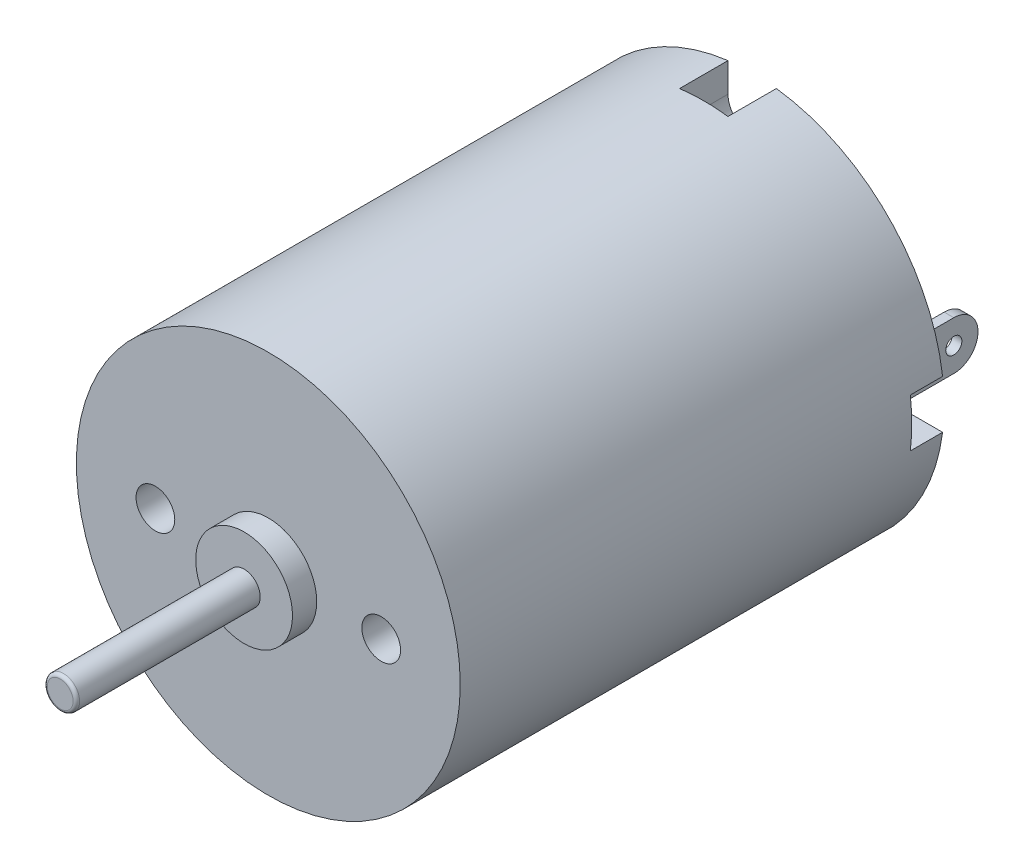
SolidWorks part; units mm, degrees
ref_plane "Alzado" through (0, 0, 0) normal (0, 0, 1) x (1, 0, 0)
ref_plane "Planta" through (0, 0, 0) normal (0, 1, 0) x (1, 0, 0)
ref_plane "Vista lateral" through (0, 0, 0) normal (1, 0, 0) x (0, 0, -1)
sketch "Croquis2" plane through (0, 0, 0) normal (0, 0, 1) x (1, 0, 0)
  circle A0 centre (0, 0) radius 11.9
  dimension "D1" = 23.8
extrude "Saliente-Extruir1" add sketch "Croquis2" along normal blind 30
sketch "Croquis3" plane through (0, 0, 30) normal (0, 0, 1) x (1, 0, 0)
  circle A0 centre (0, 0) radius 3
extrude "Saliente-Extruir2" add sketch "Croquis3" along normal blind 1.5
sketch "Croquis4" plane through (0, 0, 31.5) normal (0, 0, 1) x (1, 0, 0)
  circle A0 centre (0, 0) radius 1
  dimension "D1" = 2
extrude "Cortar-Extruir1" cut sketch "Croquis4" against normal through all
sketch "Croquis5" plane through (0, 0, 30) normal (0, 0, 1) x (1, 0, 0)
  line L0 (0, 0) -> (-5.8, 0) construction
  line L1 (0, 0) -> (5.8, 0)
  line L2 (-8.2, 0) -> (-5.8, 0) construction
  line L3 (5.8, 0) -> (8.2, 0) construction
  line L4 (-5.8, 0) -> (5.8, 0) construction
  circle A0 centre (-7, 0) radius 1.2
  circle A1 centre (7, 0) radius 1.2
  dimension "D1" = 2.4
  dimension "D2" = 5.8
  dimension "D3" = 5.8
extrude "Cortar-Extruir2" cut sketch "Croquis5" against normal blind 5 contours A1 | A0
sketch "Croquis7" plane through (0, 0, 0) normal (0, 0, -1) x (-1, 0, 0)
  circle A0 centre (0, 0) radius 4.5
  dimension "D1" = 9
extrude "Saliente-Extruir3" add sketch "Croquis7" along normal blind 1.7
sketch "Croquis8" plane through (0, 0, -1.7) normal (0, 0, -1) x (-1, 0, 0)
  circle A0 centre (0, 0) radius 1
  dimension "D1" = 2
extrude "Cortar-Extruir3" cut sketch "Croquis8" against normal up to next
sketch "Croquis9" plane through (0, 0, 0) normal (0, 0, -1) x (-1, 0, 0)
  line L0 (0, 0) -> (-9, 0) construction
  line L1 (-9, 0) -> (9, 0) construction
  line L2 (-9, 0) -> (-9, 1.5)
  line L3 (-9, 1.5) -> (-8.4, 1.5)
  line L4 (-8.4, 1.5) -> (-8.4, -1.5)
  line L5 (-8.4, -1.5) -> (-9, -1.5)
  line L6 (-9, -1.5) -> (-9, 0)
  line L7 (9, 0) -> (9, 1.5)
  line L8 (9, 1.5) -> (8.4, 1.5)
  line L9 (8.4, 1.5) -> (8.4, -1.5)
  line L10 (8.4, -1.5) -> (9, -1.5)
  line L11 (9, -1.5) -> (9, 0)
  dimension "D1" = 9
  dimension "D2" = 18
  dimension "D3" = 1.5
  dimension "D4" = 3
  dimension "D5" = 0.6
  dimension "D6" = 1.5
  dimension "D7" = 3
  dimension "D8" = 0.6
extrude "Saliente-Extruir4" add sketch "Croquis9" along normal blind 5
sketch "Croquis10" plane through (-9, 0, 0) normal (-1, 0, 0) x (0, 0, 1)
  line L0 (-5, -1.5) -> (-5, 1.5) construction
  line L1 (-3.5, -1.5) -> (-5, -1.5)
  line L2 (-5, -1.5) -> (-5, 1.5)
  line L3 (-5, 1.5) -> (-3.5, 1.5)
  arc A0 (-3.5, 1.5) -> (-3.5, -1.5) centre (-3.5, 0) ccw
  circle A1 centre (-3.5, 0) radius 0.5
  line M4 (0, 1.5) -> (-5, 1.5)
  line M5 (-5, 1.5) -> (-5, -1.5)
  line M6 (-5, -1.5) -> (0, -1.5)
  dimension "D1" = 3
extrude "Cortar-Extruir4" cut sketch "Croquis10" against normal up to surface (18 mm away) contours A0 L2 M6 | A0 M4 M5 | A1 up to face at (9, 0, -2.5)
sketch "Croquis11" plane through (0, 0, 0) normal (0, 0, -1) x (-1, 0, 0)
  line L0 (0, 0) -> (0, 8.5) construction
  line L1 (0, 8.5) -> (0, -8.5) construction
  line L2 (-1.5, -10) -> (-1.5, -12.5447)
  line L3 (-1.5, -12.5447) -> (1.5, -12.5447)
  line L4 (1.5, -12.5447) -> (1.5, -10)
  line L5 (-1.5, 10) -> (-1.5, 12.8456)
  line L6 (-1.5, 12.8456) -> (1.5, 12.8456)
  line L7 (1.5, 12.8456) -> (1.5, 10)
  arc A0 (1.5, -10) -> (-1.5, -10) centre (0, -10) ccw
  arc A1 (-1.5, 10) -> (1.5, 10) centre (0, 10) ccw
  dimension "D3" = 3
  dimension "D4" = 3
  dimension "D1" = 8.5
  dimension "D2" = 17
extrude "Cortar-Extruir5" cut sketch "Croquis11" against normal blind 3
sketch "Croquis12" plane through (0, 0, 0) normal (0, 0, -1) x (-1, 0, 0)
  line L0 (-2, 5.108) -> (-2, 7.746)
  line L2 (2, 5.108) -> (2, 7.746)
  line L3 (-2, 5.108) -> (-2, 4.0311)
  line L5 (2, 4.0311) -> (2, 5.108)
  line L6 (-2, -4.0311) -> (-2, -7.746)
  line L8 (2, -7.746) -> (2, -4.0311)
  line L9 (9, 1.5) -> (7.8581, 1.5)
  line L10 (7.5523, 1.5) -> (11.8051, 1.5)
  line L11 (9, -1.5) -> (7.8581, -1.5)
  line L12 (7.8581, -1.5) -> (11.8051, -1.5)
  line L13 (9, 1.5) -> (9, -1.5)
  line L14 (8.4, -1.5) -> (8.4, 1.5)
  line L15 (-8.4, 1.5) -> (-11.8051, 1.5)
  line L16 (-11.8051, 1.5) -> (-7.8581, 1.5)
  line L17 (-8.4, -1.5) -> (-11.8051, -1.5)
  line L18 (-11.8051, -1.5) -> (-7.8581, -1.5)
  line L19 (-8.4, 1.5) -> (-8.4, -1.5)
  line L20 (-9, -1.5) -> (-9, 1.5)
  arc A0 (-2, 7.746) -> (-7.8581, 1.5) centre (0, 0) ccw
  arc A1 (-2, 7.746) -> (7.8581, -1.5) centre (0, 0) ccw
  arc A2 (2, -4.0311) -> (2, 4.0311) centre (0, 0) ccw
  arc A3 (2, -7.746) -> (7.8581, -1.5) centre (0, 0) ccw
  arc A4 (-2, 4.0311) -> (-2, -4.0311) centre (0, 0) ccw
  arc A5 (-11.8051, 1.5) -> (-11.8051, -1.5) centre (0, 0) ccw
  arc A6 (7.8581, 1.5) -> (2, 7.746) centre (0, 0) ccw
  arc A7 (7.8581, 1.5) -> (2, 7.746) centre (0, 0) ccw
  arc A8 (-7.8581, -1.5) -> (-2, -7.746) centre (0, 0) ccw
  arc A9 (11.8051, -1.5) -> (11.8051, 1.5) centre (0, 0) ccw
  dimension "D1" = 16
extrude "Cortar-Extruir7" cut sketch "Croquis12" against normal blind 2
sketch "Croquis13" plane through (0, 0, 2) normal (0, 0, -1) x (-1, 0, 0)
  line L0 (2, 4.5826) -> (2, 4.0311)
  line L1 (2, -4.0311) -> (2, -4.5826)
  line L2 (-2, -4.5826) -> (-2, -4.0311)
  line L3 (-2, 4.0311) -> (-2, 4.5826)
  arc A0 (2, -4.5826) -> (2, 4.5826) centre (0, 0) ccw
  arc A1 (2, -4.0311) -> (2, 4.0311) centre (0, 0) ccw
  arc A2 (-2, 4.5826) -> (-2, -4.5826) centre (0, 0) ccw
  arc A3 (-2, 4.0311) -> (-2, -4.0311) centre (0, 0) ccw
  dimension "D1" = 10
extrude "Saliente-Extruir5" add sketch "Croquis13" along normal blind 1
sketch "Croquis14" plane through (0, 0, 31.5) normal (0, 0, 1) x (1, 0, 0)
  circle A0 centre (0, 0) radius 1
sketch "Croquis16" plane through (0, 0, -1.7) normal (0, 0, -1) x (-1, 0, 0)
  circle A0 centre (0, 0) radius 1
extrude "Saliente-Extruir8" add sketch "Croquis16" along normal blind 0.4 separate body
sketch "Croquis17" plane through (0, 0, -2.1) normal (0, 0, -1) x (-1, 0, 0)
  circle A0 centre (0, 0) radius 1
extrude "Saliente-Extruir9" add sketch "Croquis17" against normal blind 45
fillet "Redondeo4" radius 0.2 2 edges at (-1, 0, 42.9) (-1, 0, -2.1)
